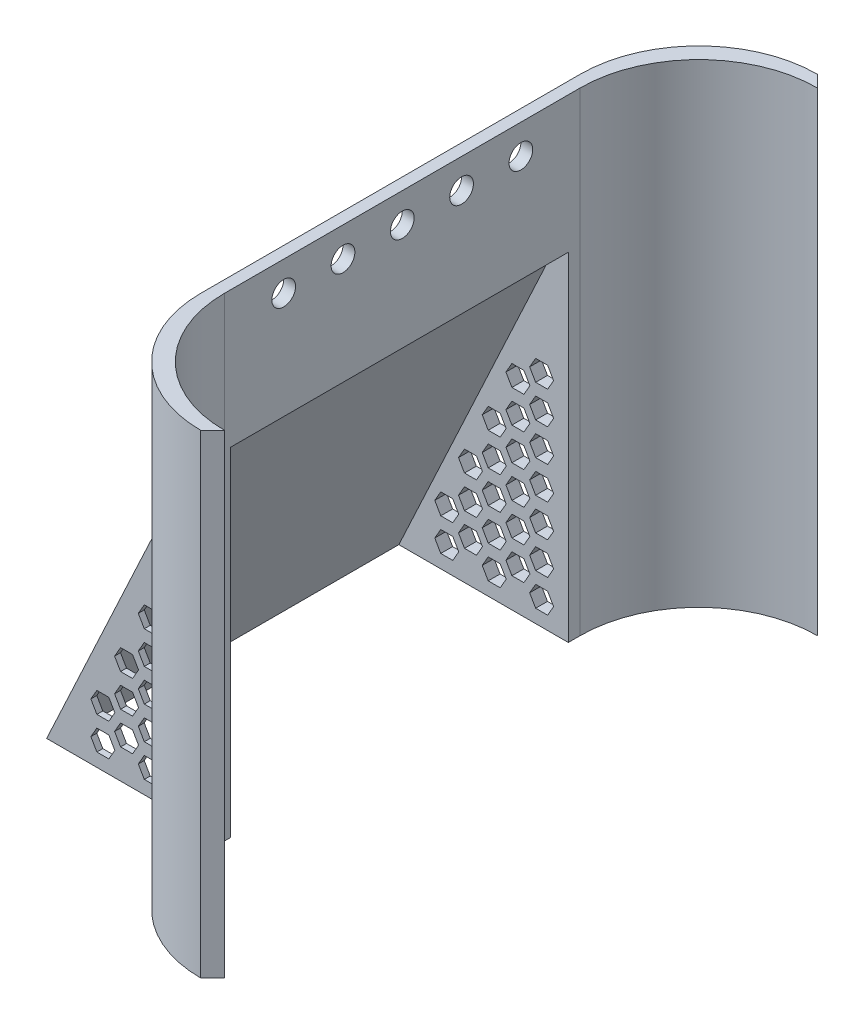
SolidWorks part; units mm, degrees
ref_plane "Ön Düzlem" through (0, 0, 0) normal (0, 0, 1) x (1, 0, 0)
ref_plane "Üst Düzlem" through (0, 0, 0) normal (0, 1, 0) x (1, 0, 0)
ref_plane "Sağ Düzlem" through (0, 0, 0) normal (1, 0, 0) x (0, 0, -1)
sketch "Çizim1" plane through (0, 0, 0) normal (0, 1, 0) x (1, 0, 0)
  line L0 (-23.4919, 10.7307) -> (-23.4919, -49.2693)
  line L7 (-25.4919, -51.2693) -> (-25.4919, 12.7307)
  line L9 (-5.4919, 32.7307) -> (-3.4919, 30.7307)
  line L10 (-5.4919, -71.2693) -> (-3.4919, -69.2693)
  arc A0 (-3.4919, 30.7307) -> (-23.4919, 10.7307) centre (-3.4919, 10.7307) ccw
  arc A1 (-23.4919, -49.2693) -> (-3.4919, -69.2693) centre (-3.4919, -49.2693) ccw
  arc A2 (-5.4919, -71.2693) -> (-25.4919, -51.2693) centre (-5.4919, -51.2693) cw
  arc A3 (-25.4919, 12.7307) -> (-5.4919, 32.7307) centre (-5.4919, 12.7307) cw
  dimension "D1" = 20
  dimension "D3" = 20
  dimension "D2" = 20
extrude "Yükseklik-Ekstrüzyon1" add sketch "Çizim1" along normal blind 80
sketch "Çizim9" plane through (-23.4919, 0, 0) normal (1, 0, 0) x (0, 0, -1)
  circle A0 centre (-29.2693, 75.0202) radius 2
  circle A1 centre (-39.2693, 75.0202) radius 2
  circle A2 centre (-9.2693, 75.0202) radius 2
  circle A3 centre (0.7307, 75.0202) radius 2
  circle A4 centre (-19.2693, 75.0202) radius 2
extrude "Kes-Ekstrüzyon1" cut sketch "Çizim9" against normal blind 3
sketch "Çizim11" plane through (-25.4919, 0, 0) normal (-1, 0, 0) x (0, 0, 1)
  line L0 (-10.7307, 0) -> (49.2693, 0)
  line L1 (-12.7307, 0) -> (51.2693, 0) construction
  line L2 (-10.7307, 0) -> (-10.7307, 60)
  line L4 (49.2693, 0) -> (49.2693, 60)
  line L5 (49.2693, 60) -> (-10.7307, 60)
extrude "Kes-Ekstrüzyon2" cut sketch "Çizim11" against normal blind 10
sketch "Çizim13" plane through (0, 0, -10.7307) normal (0, 0, 1) x (1, 0, 0)
  line L0 (-25.4919, 60) -> (-53.4704, 0)
  line L1 (-25.4919, 60) -> (-25.4919, 57)
  line L3 (-52.0714, 0) -> (-53.4704, 0)
  line L4 (-25.4919, 80) -> (-25.4919, 0) construction
  line L5 (-25.4919, 57) -> (-52.0714, 0)
extrude "Yükseklik-Ekstrüzyon2" add sketch "Çizim13" along normal blind 60 separate body
sketch "Çizim14" plane through (0, 0, 49.2693) normal (0, 0, 1) x (1, 0, 0)
  line L1 (-25.4919, 0) -> (-53.4704, 0)
  line L2 (-53.4704, 0) -> (-25.4919, 60)
  line L3 (-25.4919, 60) -> (-25.4919, 0)
  point P4 (0, 0)
extrude "Yükseklik-Ekstrüzyon6" add sketch "Çizim14" against normal blind 1
sketch "Çizim16" plane through (0, 0, -10.7307) normal (0, 0, -1) x (-1, 0, 0)
  line L0 (25.4919, 60) -> (25.4919, 0)
  line L1 (25.4919, 0) -> (53.4704, 0)
  line L2 (53.4704, 0) -> (25.4919, 60)
extrude "Yükseklik-Ekstrüzyon7" add sketch "Çizim16" against normal blind 2
sketch "Çizim17" plane through (-25.4919, 0, 0) normal (1, 0, 0) x (0, 0, -1)
  line L0 (-48.2693, 0) -> (-49.2693, 0)
  line L1 (-49.2693, 0) -> (-49.2693, 60)
  line L2 (-49.2693, 60) -> (10.7307, 60)
  line L3 (10.7307, 60) -> (10.7307, 0)
  line L4 (10.7307, 0) -> (8.7307, 0)
  line L5 (8.7307, 0) -> (8.7307, 57)
  line L6 (8.7307, 57) -> (-48.2693, 57)
  line L7 (-48.2693, 57) -> (-48.2693, 0)
extrude "Yükseklik-Ekstrüzyon8" add sketch "Çizim17" along normal blind 2
sketch "Çizim18" plane through (0, 0, 49.2693) normal (0, 0, 1) x (1, 0, 0)
  line L0 (-26.9815, 11.25) -> (-25.9712, 9.5)
  line L2 (-25.9712, 15) -> (-26.9815, 16.75)
  line L3 (-29.0023, 11.25) -> (-26.9815, 11.25)
  line L4 (-25.9712, 4) -> (-26.9815, 5.75)
  line L5 (-26.9815, 5.75) -> (-29.0023, 5.75)
  line L6 (-29.0023, 5.75) -> (-30.0126, 4)
  line L7 (-30.0126, 4) -> (-29.0023, 2.25)
  line L8 (-29.0023, 2.25) -> (-26.9815, 2.25)
  line L9 (-26.9815, 2.25) -> (-25.9712, 4)
  line L10 (-30.0126, 9.5) -> (-29.0023, 11.25)
  line L11 (-29.0023, 7.75) -> (-30.0126, 9.5)
  line L12 (-26.9815, 7.75) -> (-29.0023, 7.75)
  line L13 (-25.9712, 9.5) -> (-26.9815, 7.75)
  line L14 (-26.9815, 33.25) -> (-25.9712, 31.5)
  line L15 (-26.9815, 16.75) -> (-29.0023, 16.75)
  line L16 (-29.0023, 16.75) -> (-30.0126, 15)
  line L17 (-30.0126, 15) -> (-29.0023, 13.25)
  line L18 (-26.9815, 22.25) -> (-25.9712, 20.5)
  line L19 (-29.0023, 22.25) -> (-26.9815, 22.25)
  line L20 (-30.0126, 20.5) -> (-29.0023, 22.25)
  line L21 (-29.0023, 18.75) -> (-30.0126, 20.5)
  line L22 (-26.9815, 18.75) -> (-29.0023, 18.75)
  line L23 (-25.9712, 20.5) -> (-26.9815, 18.75)
  line L24 (-29.0023, 13.25) -> (-26.9815, 13.25)
  line L25 (-26.9815, 13.25) -> (-25.9712, 15)
  line L27 (-29.0023, 33.25) -> (-26.9815, 33.25)
  line L28 (-25.9712, 26) -> (-26.9815, 27.75)
  line L29 (-26.9815, 27.75) -> (-29.0023, 27.75)
  line L30 (-29.0023, 27.75) -> (-30.0126, 26)
  line L31 (-30.0126, 26) -> (-29.0023, 24.25)
  line L32 (-29.0023, 24.25) -> (-26.9815, 24.25)
  line L33 (-26.9815, 24.25) -> (-25.9712, 26)
  line L34 (-30.0126, 31.5) -> (-29.0023, 33.25)
  line L35 (-29.0023, 29.75) -> (-30.0126, 31.5)
  line L36 (-26.9815, 29.75) -> (-29.0023, 29.75)
  line L37 (-25.9712, 37) -> (-26.9815, 38.75)
  line L38 (-26.9815, 38.75) -> (-29.0023, 38.75)
  line L39 (-29.0023, 38.75) -> (-30.0126, 37)
  line L40 (-30.0126, 37) -> (-29.0023, 35.25)
  line L41 (-29.0023, 35.25) -> (-26.9815, 35.25)
  line L42 (-25.9712, 31.5) -> (-26.9815, 29.75)
  line L43 (-26.9815, 35.25) -> (-25.9712, 37)
  line L44 (-30.9815, 14) -> (-29.9712, 12.25)
  line L45 (-29.9712, 17.75) -> (-30.9815, 19.5)
  line L46 (-29.9712, 6.75) -> (-30.9815, 8.5)
  line L47 (-30.9815, 8.5) -> (-33.0023, 8.5)
  line L48 (-33.0023, 8.5) -> (-34.0126, 6.75)
  line L49 (-34.0126, 6.75) -> (-33.0023, 5)
  line L50 (-33.0023, 5) -> (-30.9815, 5)
  line L51 (-30.9815, 5) -> (-29.9712, 6.75)
  line L52 (-33.0023, 14) -> (-30.9815, 14)
  line L53 (-34.0126, 12.25) -> (-33.0023, 14)
  line L54 (-33.0023, 10.5) -> (-34.0126, 12.25)
  line L55 (-30.9815, 10.5) -> (-33.0023, 10.5)
  line L56 (-29.9712, 12.25) -> (-30.9815, 10.5)
  line L57 (-30.9815, 36) -> (-29.9712, 34.25)
  line L58 (-30.9815, 19.5) -> (-33.0023, 19.5)
  line L59 (-33.0023, 19.5) -> (-34.0126, 17.75)
  line L60 (-34.0126, 17.75) -> (-33.0023, 16)
  line L61 (-33.0023, 16) -> (-30.9815, 16)
  line L62 (-30.9815, 25) -> (-29.9712, 23.25)
  line L63 (-33.0023, 25) -> (-30.9815, 25)
  line L64 (-34.0126, 23.25) -> (-33.0023, 25)
  line L65 (-33.0023, 21.5) -> (-34.0126, 23.25)
  line L66 (-30.9815, 21.5) -> (-33.0023, 21.5)
  line L67 (-29.9712, 23.25) -> (-30.9815, 21.5)
  line L68 (-30.9815, 16) -> (-29.9712, 17.75)
  line L70 (-29.9712, 28.75) -> (-30.9815, 30.5)
  line L71 (-30.9815, 30.5) -> (-33.0023, 30.5)
  line L72 (-33.0023, 30.5) -> (-34.0126, 28.75)
  line L73 (-34.0126, 28.75) -> (-33.0023, 27)
  line L74 (-33.0023, 27) -> (-30.9815, 27)
  line L75 (-30.9815, 27) -> (-29.9712, 28.75)
  line L76 (-33.0023, 36) -> (-30.9815, 36)
  line L77 (-34.0126, 34.25) -> (-33.0023, 36)
  line L78 (-33.0023, 32.5) -> (-34.0126, 34.25)
  line L79 (-30.9815, 32.5) -> (-33.0023, 32.5)
  line L80 (-29.9712, 34.25) -> (-30.9815, 32.5)
  line L81 (-37.0023, 24.25) -> (-38.0126, 26)
  line L82 (-34.9815, 24.25) -> (-37.0023, 24.25)
  line L83 (-33.9712, 26) -> (-34.9815, 24.25)
  line L84 (-34.9815, 27.75) -> (-33.9712, 26)
  line L85 (-37.0023, 27.75) -> (-34.9815, 27.75)
  line L86 (-38.0126, 26) -> (-37.0023, 27.75)
  line L87 (-41.0023, 16) -> (-42.0126, 17.75)
  line L88 (-37.0023, 13.25) -> (-38.0126, 15)
  line L89 (-34.9815, 13.25) -> (-37.0023, 13.25)
  line L90 (-38.0126, 20.5) -> (-37.0023, 18.75)
  line L91 (-37.0023, 18.75) -> (-34.9815, 18.75)
  line L92 (-34.9815, 18.75) -> (-33.9712, 20.5)
  line L93 (-33.9712, 20.5) -> (-34.9815, 22.25)
  line L94 (-34.9815, 22.25) -> (-37.0023, 22.25)
  line L95 (-37.0023, 22.25) -> (-38.0126, 20.5)
  line L96 (-33.9712, 15) -> (-34.9815, 13.25)
  line L97 (-34.9815, 16.75) -> (-33.9712, 15)
  line L98 (-37.0023, 16.75) -> (-34.9815, 16.75)
  line L99 (-38.0126, 9.5) -> (-37.0023, 7.75)
  line L100 (-37.0023, 7.75) -> (-34.9815, 7.75)
  line L101 (-34.9815, 7.75) -> (-33.9712, 9.5)
  line L102 (-33.9712, 9.5) -> (-34.9815, 11.25)
  line L103 (-37.0023, 2.25) -> (-38.0126, 4)
  line L104 (-34.9815, 2.25) -> (-37.0023, 2.25)
  line L105 (-33.9712, 4) -> (-34.9815, 2.25)
  line L106 (-34.9815, 5.75) -> (-33.9712, 4)
  line L107 (-37.0023, 5.75) -> (-34.9815, 5.75)
  line L108 (-38.0126, 4) -> (-37.0023, 5.75)
  line L109 (-34.9815, 11.25) -> (-37.0023, 11.25)
  line L110 (-38.0126, 15) -> (-37.0023, 16.75)
  line L111 (-37.0023, 11.25) -> (-38.0126, 9.5)
  line L112 (-38.9815, 16) -> (-41.0023, 16)
  line L113 (-37.9712, 17.75) -> (-38.9815, 16)
  line L114 (-38.9815, 19.5) -> (-37.9712, 17.75)
  line L115 (-41.0023, 19.5) -> (-38.9815, 19.5)
  line L116 (-42.0126, 12.25) -> (-41.0023, 10.5)
  line L117 (-41.0023, 10.5) -> (-38.9815, 10.5)
  line L118 (-38.9815, 10.5) -> (-37.9712, 12.25)
  line L119 (-37.9712, 12.25) -> (-38.9815, 14)
  line L120 (-38.9815, 14) -> (-41.0023, 14)
  line L121 (-41.0023, 5) -> (-42.0126, 6.75)
  line L122 (-38.9815, 5) -> (-41.0023, 5)
  line L123 (-37.9712, 6.75) -> (-38.9815, 5)
  line L124 (-38.9815, 8.5) -> (-37.9712, 6.75)
  line L125 (-41.0023, 8.5) -> (-38.9815, 8.5)
  line L126 (-42.0126, 6.75) -> (-41.0023, 8.5)
  line L127 (-42.0126, 17.75) -> (-41.0023, 19.5)
  line L128 (-41.0023, 14) -> (-42.0126, 12.25)
  line L129 (-42.9815, 11.25) -> (-41.9712, 9.5)
  line L130 (-45.0023, 11.25) -> (-42.9815, 11.25)
  line L131 (-41.9712, 4) -> (-42.9815, 5.75)
  line L132 (-42.9815, 5.75) -> (-45.0023, 5.75)
  line L133 (-45.0023, 5.75) -> (-46.0126, 4)
  line L134 (-46.0126, 4) -> (-45.0023, 2.25)
  line L135 (-45.0023, 2.25) -> (-42.9815, 2.25)
  line L136 (-42.9815, 2.25) -> (-41.9712, 4)
  line L137 (-46.0126, 9.5) -> (-45.0023, 11.25)
  line L138 (-45.0023, 7.75) -> (-46.0126, 9.5)
  line L139 (-42.9815, 7.75) -> (-45.0023, 7.75)
  line L140 (-41.9712, 9.5) -> (-42.9815, 7.75)
  circle A0 centre (-27.9919, 4) radius 1.75 construction
  circle A1 centre (-27.9919, 9.5) radius 1.75 construction
  circle A2 centre (-27.9919, 15) radius 1.75 construction
  circle A3 centre (-27.9919, 20.5) radius 1.75 construction
  circle A4 centre (-27.9919, 26) radius 1.75 construction
  circle A5 centre (-27.9919, 31.5) radius 1.75 construction
  circle A6 centre (-27.9919, 37) radius 1.75 construction
  circle A7 centre (-31.9919, 6.75) radius 1.75 construction
  circle A8 centre (-31.9919, 12.25) radius 1.75 construction
  circle A9 centre (-31.9919, 17.75) radius 1.75 construction
  circle A10 centre (-31.9919, 23.25) radius 1.75 construction
  circle A11 centre (-31.9919, 28.75) radius 1.75 construction
  circle A12 centre (-31.9919, 34.25) radius 1.75 construction
  circle A13 centre (-35.9919, 26) radius 1.75 construction
  circle A14 centre (-35.9919, 20.5) radius 1.75 construction
  circle A15 centre (-35.9919, 15) radius 1.75 construction
  circle A16 centre (-35.9919, 9.5) radius 1.75 construction
  circle A17 centre (-35.9919, 4) radius 1.75 construction
  circle A18 centre (-39.9919, 17.75) radius 1.75 construction
  circle A19 centre (-39.9919, 12.25) radius 1.75 construction
  circle A20 centre (-39.9919, 6.75) radius 1.75 construction
  circle A21 centre (-43.9919, 4) radius 1.75 construction
  circle A22 centre (-43.9919, 9.5) radius 1.75 construction
  dimension "D1" = 3.5
  dimension "D2" = 3.5
extrude "Kes-Ekstrüzyon3" cut sketch "Çizim18" against normal blind 86
